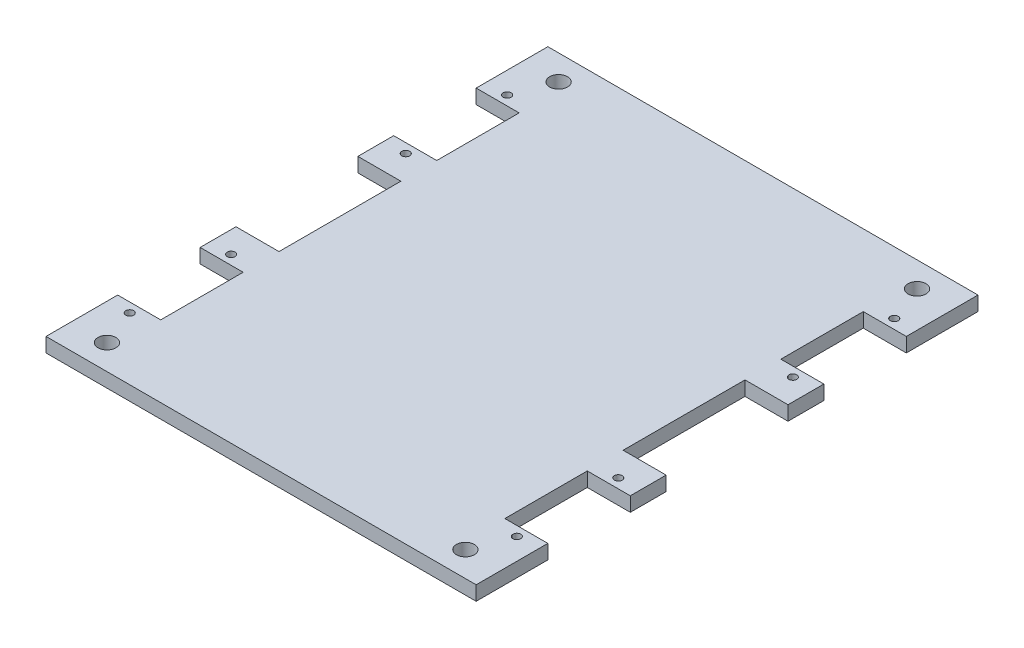
SolidWorks part; units mm, degrees
material "1060 Alloy"
ref_plane "Front Plane" through (0, 0, 0) normal (0, 0, 1) x (1, 0, 0)
ref_plane "Top Plane" through (0, 0, 0) normal (0, 1, 0) x (1, 0, 0)
ref_plane "Right Plane" through (0, 0, 0) normal (1, 0, 0) x (0, 0, -1)
sketch "Sketch1" plane through (0, 0, 0) normal (0, 1, 0) x (1, 0, 0)
  line L1 (-60, -70) -> (60, -70)
  line L2 (-60, -70) -> (-60, 70)
  line L3 (-60, 70) -> (60, 70)
  line L4 (60, -70) -> (60, 70)
  line L5 (-60, -70) -> (60, 70) construction
  line L6 (-60, 70) -> (60, -70) construction
  point P0 (0, 0)
  dimension "D1" = 140
  dimension "D2" = 120
extrude "Boss-Extrude1" add sketch "Sketch1" along normal blind 4
sketch "Sketch2" plane through (0, 4, 0) normal (0, 1, 0) x (1, 0, 0)
  line L0 (60, -70) -> (60, 70) construction
  line L1 (60, 50) -> (48, 50)
  line L2 (60, 50) -> (60, 27)
  line L3 (60, 27) -> (48, 27)
  line L4 (48, 50) -> (48, 27)
  line L5 (-60, 70) -> (-60, -70) construction
  line L6 (-60, 50) -> (-48, 50)
  line L7 (-60, 50) -> (-60, 27)
  line L8 (-60, 27) -> (-48, 27)
  line L9 (-48, 50) -> (-48, 27)
  line L10 (-48, 0) -> (0, 0) construction
  line L19 (60, -27) -> (48, -27)
  line L20 (60, -27) -> (60, -50)
  line L21 (60, -50) -> (48, -50)
  line L22 (48, -27) -> (48, -50)
  line L23 (-60, -27) -> (-48, -27)
  line L24 (-60, -27) -> (-60, -50)
  line L25 (-60, -50) -> (-48, -50)
  line L26 (-48, -27) -> (-48, -50)
  line L27 (0, 0) -> (48, 0) construction
  line L28 (-54, 52.65) -> (-54, 50) construction
  line L29 (-60, -70) -> (60, -70) construction
  line L30 (60, 70) -> (-60, 70) construction
  line L31 (-54, 24.35) -> (-54, 27) construction
  line L32 (-60, 17) -> (-48, 17)
  line L33 (-60, 17) -> (-60, -17)
  line L34 (-60, -17) -> (-48, -17)
  line L35 (-48, 17) -> (-48, -17)
  line L36 (60, 17) -> (48, 17)
  line L37 (60, 17) -> (60, -17)
  line L38 (60, -17) -> (48, -17)
  line L39 (48, 17) -> (48, -17)
  line L40 (-54, -24.35) -> (-54, -27) construction
  line L41 (-54, -50) -> (-54, -52.65) construction
  line L42 (54, 52.65) -> (54, 50) construction
  line L43 (54, 24.35) -> (54, 27) construction
  line L44 (54, -24.35) -> (54, -27) construction
  line L45 (54, -50) -> (54, -52.65) construction
  circle A2 centre (-54, 52.65) radius 1.1
  circle A3 centre (-54, 24.35) radius 1.1
  circle A4 centre (-54, -24.35) radius 1.1
  circle A5 centre (-54, -52.65) radius 1.1
  circle A6 centre (54, 52.65) radius 1.1
  circle A7 centre (54, 24.35) radius 1.1
  circle A8 centre (54, -24.35) radius 1.1
  circle A9 centre (54, -52.65) radius 1.1
  circle A10 centre (-50, 63) radius 2.5
  circle A11 centre (50, 63) radius 2.5
  circle A12 centre (50, -63) radius 2.5
  circle A13 centre (-50, -63) radius 2.5
  line M15 (60, -70) -> (60, 70)
  line M17 (-60, 70) -> (-60, -70)
  dimension "D6" = 2.2
  dimension "D15" = 5
  dimension "D1" = 23
  dimension "D2" = 12
  dimension "D3" = 20
  dimension "D4" = 20
  dimension "D5" = 10
  dimension "D7" = 2.65
  dimension "D8" = 2.65
  dimension "D9" = 2.65
  dimension "D10" = 2.65
  dimension "D11" = 2.65
  dimension "D12" = 2.65
  dimension "D13" = 2.65
  dimension "D14" = 2.65
  dimension "D16" = 10
  dimension "D17" = 7
  dimension "D18" = 7
  dimension "D19" = 10
  dimension "D20" = 10
  dimension "D21" = 7
  dimension "D22" = 10
  dimension "D23" = 7
extrude "Cut-Extrude1" cut sketch "Sketch2" against normal through all contours L35 L32 L34 M17 | L36 L39 L38 M15 | A2 | A3 | A4 | A5 | A8 | A9 | A6 | A7 | A10 | A11 | A13 | A12
